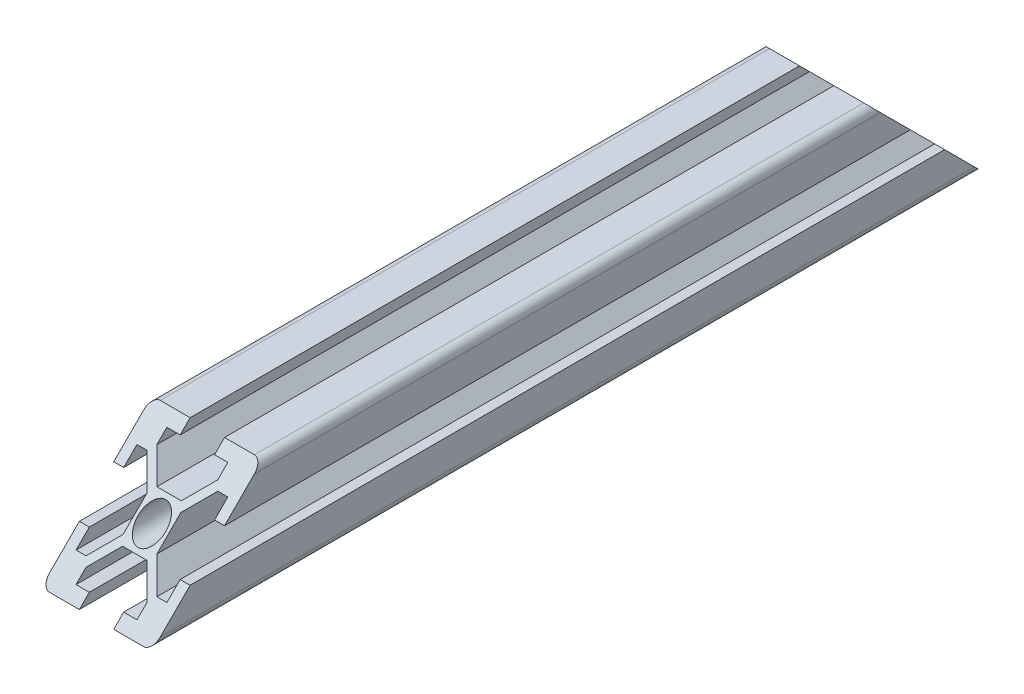
SolidWorks part; units mm, degrees
ref_plane "前视基准面" through (0, 0, 0) normal (0, 0, 1) x (1, 0, 0)
ref_plane "上视基准面" through (0, 0, 0) normal (0, 1, 0) x (1, 0, 0)
ref_plane "右视基准面" through (0, 0, 0) normal (1, 0, 0) x (0, 0, -1)
sketch "草图1" plane through (0, 0, 0) normal (0, 0, 1) x (1, 0, 0)
  line L0 (-27.7562, -9.7656) -> (-25.9562, -9.7656)
  line L1 (-26.2562, 3.3344) -> (-9.2562, 3.3344)
  line L2 (-27.7562, 1.8344) -> (-27.7562, -15.1656)
  line L3 (-26.2562, -16.6656) -> (-9.2562, -16.6656)
  line L4 (-7.7562, 1.8344) -> (-7.7562, -15.1656)
  line L5 (-27.7562, 3.3344) -> (-7.7562, -16.6656) construction
  line L6 (-27.7562, -16.6656) -> (-7.7562, 3.3344) construction
  line L7 (-20.8104, -3.5656) -> (-14.7021, -3.5656)
  line L8 (-20.8104, -3.5656) -> (-20.8104, -9.7656)
  line L9 (-20.8104, -9.7656) -> (-14.7021, -9.7656)
  line L10 (-14.7021, -3.5656) -> (-14.7021, -9.7656)
  line L11 (-20.8104, -3.5656) -> (-14.7021, -9.7656) construction
  line L12 (-20.8104, -9.7656) -> (-14.7021, -3.5656) construction
  line L13 (-25.9562, -9.7656) -> (-25.9562, -12.1656)
  line L14 (-25.9562, -12.1656) -> (-24.1533, -12.1656)
  line L15 (-24.1533, -12.1656) -> (-20.8104, -8.8227)
  line L16 (-23.2562, -0.2685) -> (-19.9133, -3.6115)
  line L17 (-23.2562, 1.5344) -> (-23.2562, -0.2685)
  line L18 (-20.8562, 1.5344) -> (-23.2562, 1.5344)
  line L19 (-20.8562, 3.3344) -> (-20.8562, 1.5344)
  line L20 (-11.3592, -1.1656) -> (-14.7021, -4.5085)
  line L21 (-9.5562, -1.1656) -> (-11.3592, -1.1656)
  line L22 (-9.5562, -3.5656) -> (-9.5562, -1.1656)
  line L23 (-7.7562, -3.5656) -> (-9.5562, -3.5656)
  line L24 (-12.2562, -13.0626) -> (-15.5992, -9.7197)
  line L25 (-12.2562, -14.8656) -> (-12.2562, -13.0626)
  line L26 (-14.6562, -14.8656) -> (-12.2562, -14.8656)
  line L27 (-14.6562, -16.6656) -> (-14.6562, -14.8656)
  line L28 (-20.8562, -16.6656) -> (-20.8562, -14.8656)
  line L29 (-20.8562, -14.8656) -> (-23.2562, -14.8656)
  line L30 (-23.2562, -14.8656) -> (-23.2562, -13.0626)
  line L31 (-23.2562, -13.0626) -> (-19.9133, -9.7197)
  line L32 (-25.9562, -1.1656) -> (-24.1533, -1.1656)
  line L33 (-24.1533, -1.1656) -> (-20.8104, -4.5085)
  line L34 (-25.9562, -3.5656) -> (-25.9562, -1.1656)
  line L35 (-27.7562, -3.5656) -> (-25.9562, -3.5656)
  line L36 (-12.2562, 1.5344) -> (-12.2562, -0.2685)
  line L37 (-12.2562, -0.2685) -> (-15.5992, -3.6115)
  line L38 (-14.6562, 1.5344) -> (-12.2562, 1.5344)
  line L39 (-14.6562, 3.3344) -> (-14.6562, 1.5344)
  line L40 (-9.5562, -12.1656) -> (-11.3592, -12.1656)
  line L41 (-11.3592, -12.1656) -> (-14.7021, -8.8227)
  line L42 (-9.5562, -9.7656) -> (-9.5562, -12.1656)
  line L43 (-7.7562, -9.7656) -> (-9.5562, -9.7656)
  circle A0 centre (-17.7562, -6.6656) radius 2.5
  arc A1 (-27.7562, 1.8344) -> (-26.2562, 3.3344) centre (-26.2562, 1.8344) cw
  arc A2 (-27.7562, -15.1656) -> (-26.2562, -16.6656) centre (-26.2562, -15.1656) ccw
  arc A3 (-9.2562, 3.3344) -> (-7.7562, 1.8344) centre (-9.2562, 1.8344) cw
  arc A4 (-7.7562, -15.1656) -> (-9.2562, -16.6656) centre (-9.2562, -15.1656) cw
  point P0 (-17.7562, -6.6656)
  point P19 (-17.7562, -6.6656)
  point P25 (-17.7562, -6.6656)
  point P31 (-17.7562, -6.6656)
  point P37 (-17.7562, -6.6656)
  point P59 (-17.7562, -6.6656)
extrude "凸台-拉伸1" add sketch "草图1" along normal blind 150
sketch "草图2" plane through (-27.7562, 0, 0) normal (-1, 0, 0) x (0, 0, 1)
  line L0 (0, -16.6656) -> (20, 3.3344)
  line L1 (150, 3.3344) -> (0, 3.3344) construction
  line L2 (150, -16.6656) -> (130, 3.3344)
  line L3 (0, -4.5085) -> (0, -8.8227) construction
  line L4 (150, -4.5085) -> (150, -8.8227) construction
  line L5 (20, 3.3344) -> (0, 3.3344)
  line L6 (0, 3.3344) -> (0, -16.6656)
  line L7 (130, 3.3344) -> (150, 3.3344)
  line L8 (150, 3.3344) -> (150, -16.6656)
  dimension "D1" = 45
  dimension "D2" = 45
extrude "切除-拉伸1" cut sketch "草图2" against normal through all
